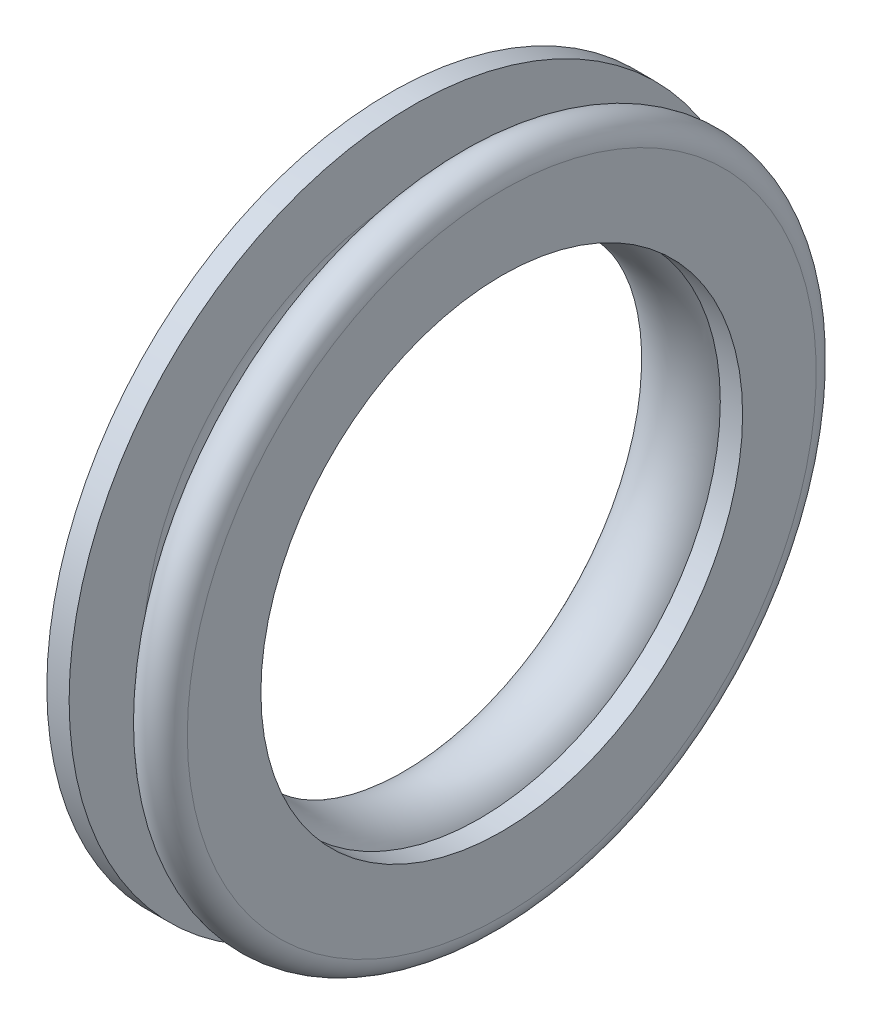
SolidWorks part; units mm, degrees
ref_plane "Front Plane" through (0, 0, 0) normal (0, 0, 1) x (1, 0, 0)
ref_plane "Top Plane" through (0, 0, 0) normal (0, 1, 0) x (1, 0, 0)
ref_plane "Right Plane" through (0, 0, 0) normal (1, 0, 0) x (0, 0, -1)
sketch "Sketch1" plane through (0, 0, 0) normal (0, 0, 1) x (1, 0, 0)
  line L0 (0, 7.7) -> (0, 0) construction
  line L1 (0, 0) -> (10.8755, 0) construction
  line L2 (0, 7.7) -> (0, 6.05)
  line L3 (2.5, 7.05) -> (2.5, 5.4)
  line L4 (2, 6.05) -> (2, 7.05) construction
  line L5 (0.5, 7.7) -> (0.5, 6.05)
  line L6 (1.5, 6.05) -> (1.5, 7.05)
  line L7 (2, 7.05) -> (2, 5.4) construction
  line L8 (0.5, 7.7) -> (0, 7.7)
  line L9 (2, 5.4) -> (2.5, 5.4)
  line L10 (2, 7.05) -> (1.5, 7.05) construction
  line L11 (2, 6.05) -> (2, 5.4)
  arc A0 (0, 6.05) -> (2, 6.05) centre (1, 6.05) ccw
  arc A2 (0.5, 6.05) -> (1.5, 6.05) centre (1, 6.05) ccw
  arc A3 (2.5, 7.05) -> (1.5, 7.05) centre (2, 7.05) ccw
  dimension "D3" = 1
  dimension "D5" = 0.5
  dimension "D1" = 7.7
  dimension "D2" = 1.65
  dimension "D4" = 1
  dimension "D6" = 1.65
  dimension "D7" = 0.5
  dimension "D8" = 0.5
revolve "Revolve1" add sketch "Sketch1" angle 360 about L1
